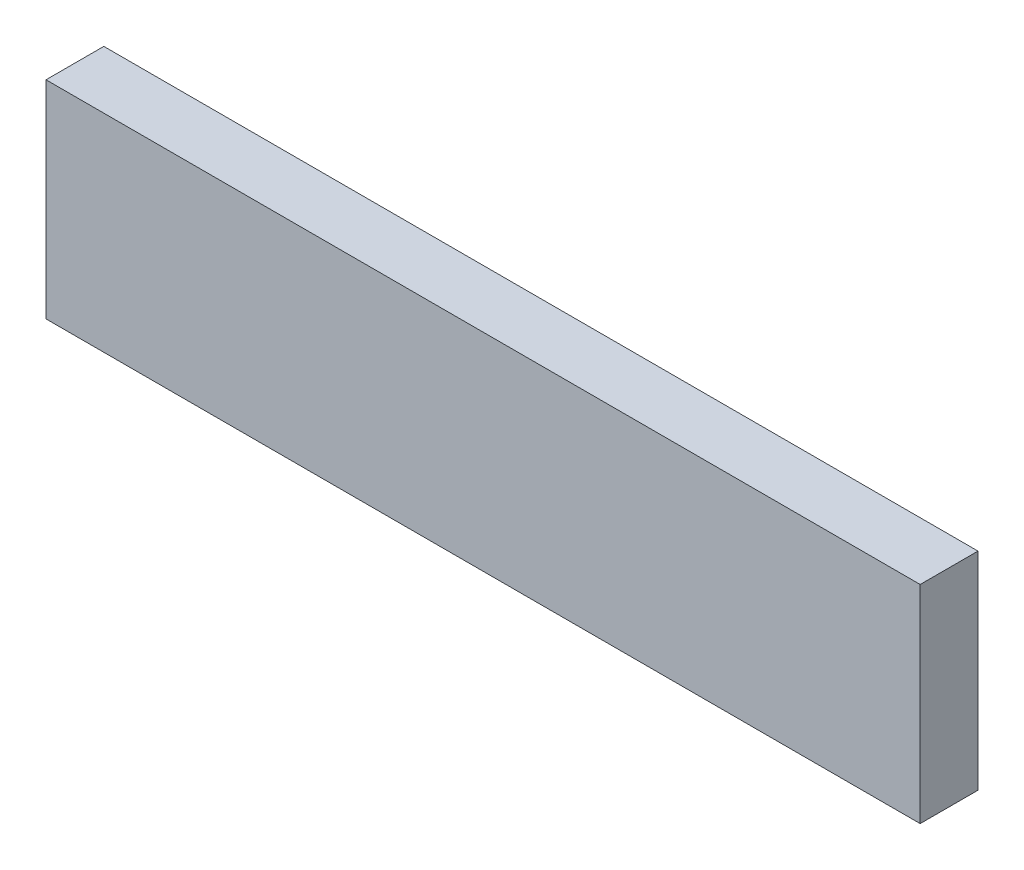
SolidWorks part; units mm, degrees
material "Acrylic (Medium-high impact)"
ref_plane "Front Plane" through (0, 0, 0) normal (0, 0, 1) x (1, 0, 0)
ref_plane "Top Plane" through (0, 0, 0) normal (0, 1, 0) x (1, 0, 0)
ref_plane "Right Plane" through (0, 0, 0) normal (1, 0, 0) x (0, 0, -1)
sketch "Sketch1" plane through (0, 0, 0) normal (0, 0, 1) x (1, 0, 0)
  line L1 (47.99, -11.37) -> (-47.99, -11.37)
  line L2 (47.99, -11.37) -> (47.99, 11.37)
  line L3 (47.99, 11.37) -> (-47.99, 11.37)
  line L4 (-47.99, -11.37) -> (-47.99, 11.37)
  line L5 (47.99, -11.37) -> (-47.99, 11.37) construction
  line L6 (47.99, 11.37) -> (-47.99, -11.37) construction
  point P0 (0, 0)
  dimension "D1" = 22.74
  dimension "D2" = 95.98
extrude "Boss-Extrude1" add sketch "Sketch1" along normal blind 6.35
